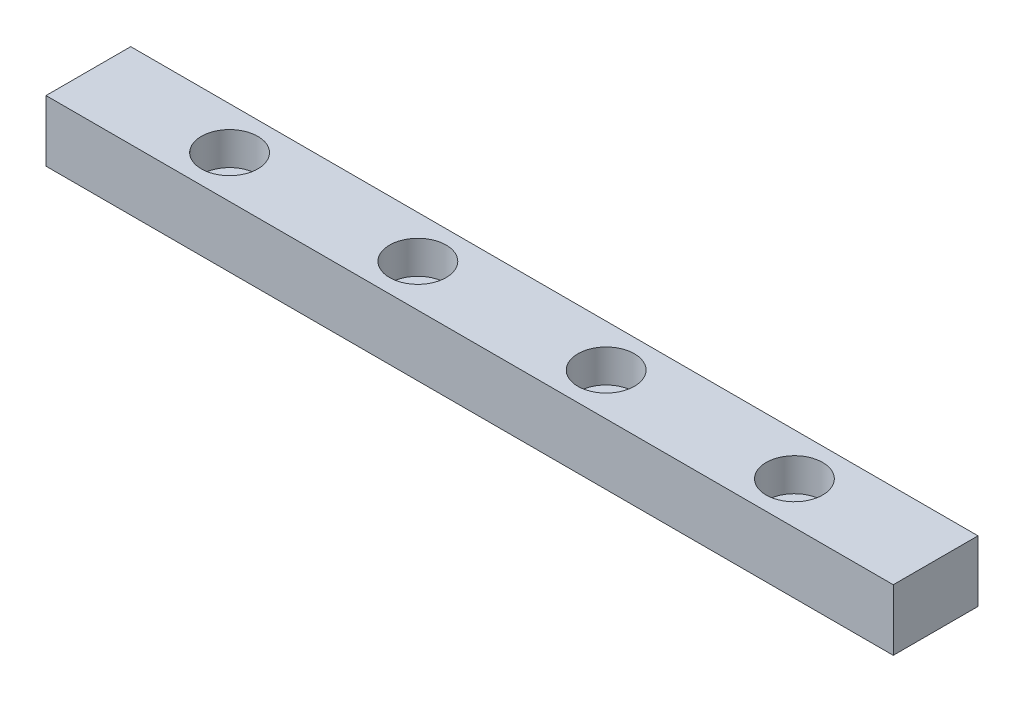
SolidWorks part; units mm, degrees
material "铸造碳钢"
ref_plane "前视基准面" through (0, 0, 0) normal (0, 0, 1) x (1, 0, 0)
ref_plane "上视基准面" through (0, 0, 0) normal (0, 1, 0) x (1, 0, 0)
ref_plane "右视基准面" through (0, 0, 0) normal (1, 0, 0) x (0, 0, -1)
sketch "草图2" plane through (0, 0, 0) normal (1, 0, 0) x (0, 0, -1)
  line L1 (-4.5, 3.25) -> (4.5, 3.25)
  line L2 (-4.5, 3.25) -> (-4.5, -3.25)
  line L3 (-4.5, -3.25) -> (4.5, -3.25)
  line L4 (4.5, 3.25) -> (4.5, -3.25)
  line L5 (-4.5, 3.25) -> (4.5, -3.25) construction
  line L6 (-4.5, -3.25) -> (4.5, 3.25) construction
  point P0 (0, 0)
  dimension "D1" = 9
  dimension "D2" = 6.5
extrude "凸台-拉伸1" add sketch "草图2" along normal blind 90
sketch "草图3" plane through (0, 3.25, 0) normal (0, 1, 0) x (1, 0, 0)
  line L0 (0, 0) -> (90, 0) construction
  line L1 (90, 4.5) -> (90, -4.5) construction
  line L2 (0, 4.5) -> (0, -4.5) construction
  circle A0 centre (15, 0) radius 3
  circle A1 centre (35, 0) radius 3
  circle A2 centre (55, 0) radius 3
  circle A3 centre (75, 0) radius 3
  circle A4 centre (95, 0) radius 3
  circle A5 centre (115, 0) radius 3
  circle A6 centre (135, 0) radius 3
  circle A7 centre (155, 0) radius 3
  circle A8 centre (175, 0) radius 3
  circle A9 centre (195, 0) radius 3
  circle A10 centre (215, 0) radius 3
  circle A11 centre (235, 0) radius 3
  circle A12 centre (255, 0) radius 3
  dimension "D1" = 15
  dimension "D2" = 6
  dimension "D4" = 20
  dimension "D3" = 13
extrude "切除-拉伸1" cut sketch "草图3" against normal blind 3.5
sketch "草图4" plane through (0, 3.25, 0) normal (0, 1, 0) x (1, 0, 0)
  line L0 (0, 0) -> (90, 0) construction
  line L1 (0, 4.5) -> (0, -4.5) construction
  circle A0 centre (15, 0) radius 1.75
  circle A1 centre (35, 0) radius 1.75
  circle A2 centre (55, 0) radius 1.75
  circle A3 centre (75, 0) radius 1.75
  circle A4 centre (95, 0) radius 1.75
  circle A5 centre (115, 0) radius 1.75
  circle A6 centre (135, 0) radius 1.75
  circle A7 centre (155, 0) radius 1.75
  circle A8 centre (175, 0) radius 1.75
  circle A9 centre (195, 0) radius 1.75
  circle A10 centre (215, 0) radius 1.75
  circle A11 centre (235, 0) radius 1.75
  circle A12 centre (255, 0) radius 1.75
  dimension "D1" = 3.5
  dimension "D3" = 20
  dimension "D2" = 13
extrude "切除-拉伸2" cut sketch "草图4" against normal through all
